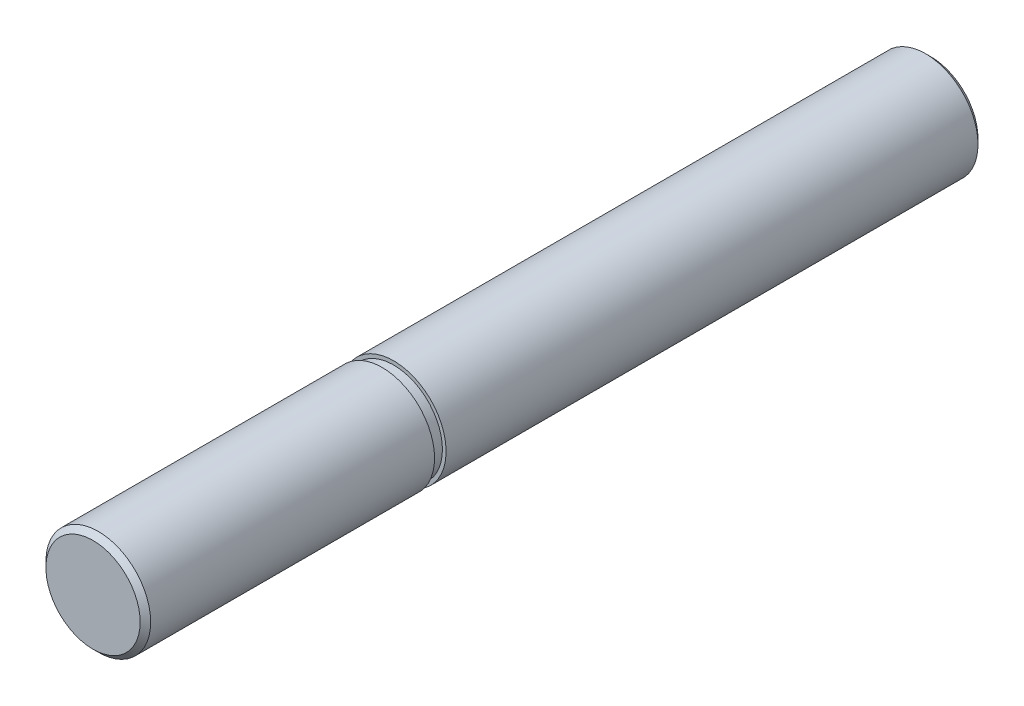
SolidWorks part; units mm, degrees
ref_plane "前视基准面" through (0, 0, 0) normal (0, 0, 1) x (1, 0, 0)
ref_plane "上视基准面" through (0, 0, 0) normal (0, 1, 0) x (1, 0, 0)
ref_plane "右视基准面" through (0, 0, 0) normal (1, 0, 0) x (0, 0, -1)
sketch "草图1" plane through (0, 0, 0) normal (0, 0, 1) x (1, 0, 0)
  circle A0 centre (0, 0) radius 5
  dimension "D1" = 10
extrude "拉伸1" add sketch "草图1" along normal blind 80
chamfer "倒角1" distance 0.5 angle 45 2 edges at (5, 0, 0) (5, 0, 80)
sketch "草图2" plane through (0, 0, 0) normal (0, 1, 0) x (1, 0, 0)
  line L0 (-12.5, -51.29) -> (12.5, -51.29) construction
  line L1 (4.65, -51.29) -> (6.87, -51.29)
  line L2 (4.65, -51.29) -> (4.65, -52.39)
  line L3 (4.65, -52.39) -> (6.87, -52.39)
  line L4 (6.87, -51.29) -> (6.87, -52.39)
  line L5 (5, -79.5) -> (5, -0.5) construction
  dimension "D1" = 0.35
  dimension "D2" = 1.1
revolve "切除-旋转1" cut sketch "草图2" angle 360 about axis through (0, 0, 80) along (0, 0, -1)
